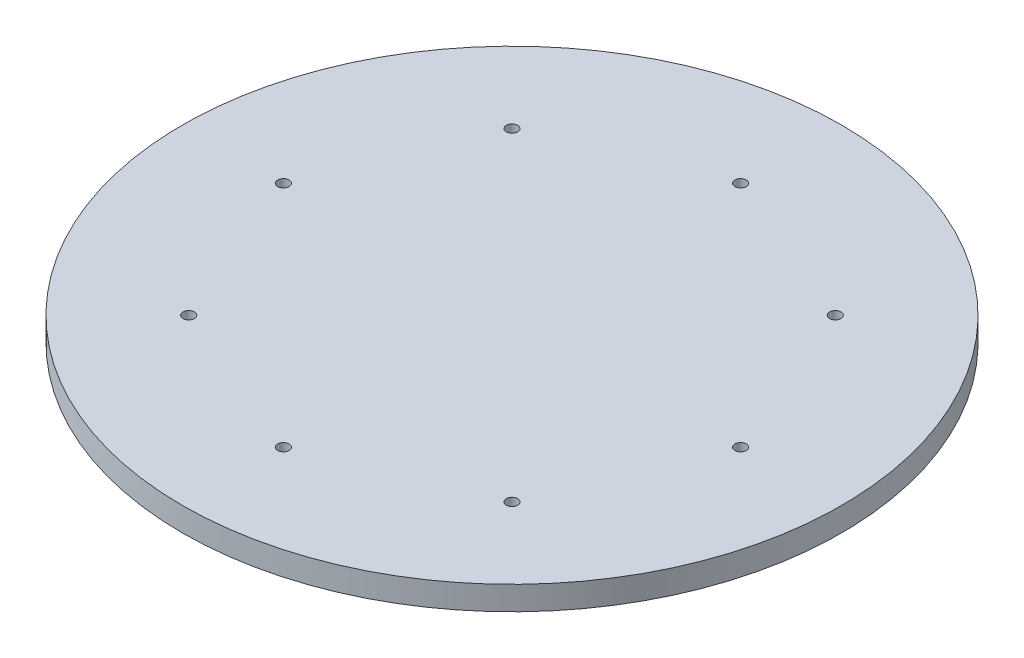
SolidWorks part; units mm, degrees
material "Custom Plastic"
ref_plane "Front Plane" through (0, 0, 0) normal (0, 0, 1) x (1, 0, 0)
ref_plane "Top Plane" through (0, 0, 0) normal (0, 1, 0) x (1, 0, 0)
ref_plane "Right Plane" through (0, 0, 0) normal (1, 0, 0) x (0, 0, -1)
sketch "Sketch1" plane through (0, 0, 0) normal (0, 1, 0) x (1, 0, 0)
  line L0 (0, -7310.1215) -> (0, 358195.9516) construction
  line L1 (-7310.1215, 0) -> (358195.9516, 0) construction
  circle A0 centre (0, 0) radius 346
  circle A2 centre (0, 240) radius 6
  circle A3 centre (169.7056, 169.7056) radius 6
  circle A4 centre (240, 0) radius 6
  circle A5 centre (169.7056, -169.7056) radius 6
  circle A6 centre (0, -240) radius 6
  circle A7 centre (-169.7056, -169.7056) radius 6
  circle A8 centre (-240, 0) radius 6
  circle A9 centre (-169.7056, 169.7056) radius 6
  point P27 (0, 0)
  dimension "D1" = 692
  dimension "D4" = 12
  dimension "D3" = 240
  dimension "D5" = 8
extrude "Boss-Extrude1" add sketch "Sketch1" along normal mid plane 25
sketch "Sketch2" plane through (0, -12.5, 0) normal (0, -1, 0) x (1, 0, 0)
  circle A0 centre (0, 0) radius 286
  circle A1 centre (0, 0) radius 317
  dimension "D1" = 572
  dimension "D2" = 634
extrude "Cut-Extrude1" cut sketch "Sketch2" against normal blind 12
